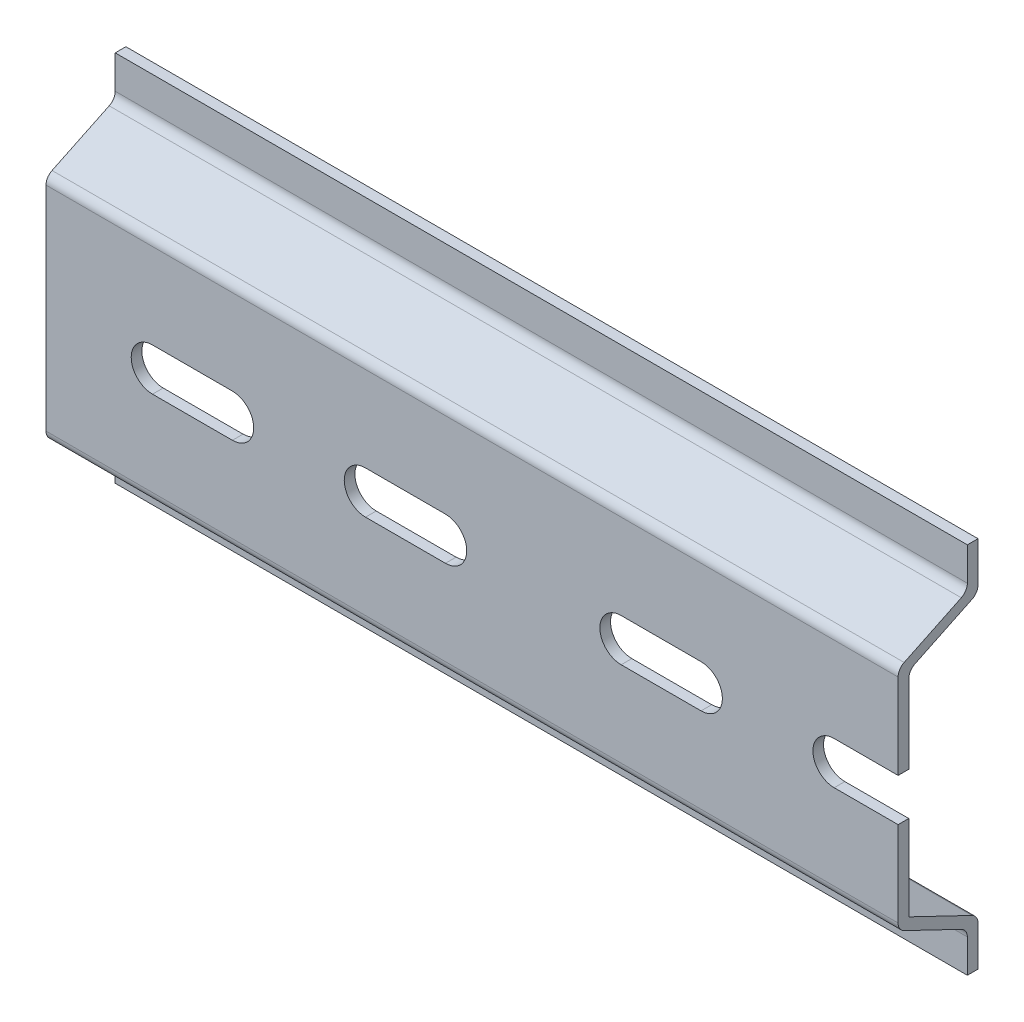
SolidWorks part; units mm, degrees
ref_plane "前视基准面" through (0, 0, 0) normal (0, 0, 1) x (1, 0, 0)
ref_plane "上视基准面" through (0, 0, 0) normal (0, 1, 0) x (1, 0, 0)
ref_plane "右视基准面" through (0, 0, 0) normal (1, 0, 0) x (0, 0, -1)
sketch "草图1" plane through (0, 0, 0) normal (1, 0, 0) x (0, 0, -1)
  line L0 (0, -10) -> (0, 10)
  line L1 (0, 10) -> (6.5, 13.1208)
  line L2 (6.5, 13.1208) -> (6.5, 17.5)
  line L3 (6.5, 17.5) -> (5.5, 17.5)
  line L4 (5.5, 17.5) -> (5.5, 13.75)
  line L5 (5.5, 13.75) -> (-1, 10.6292)
  line L6 (-1, 10.6292) -> (-1, -10.6292)
  line L7 (-14.3812, 0) -> (24.228, 0) construction
  line L8 (5.5, -13.75) -> (-1, -10.6292)
  line L9 (5.5, -17.5) -> (5.5, -13.75)
  line L10 (6.5, -17.5) -> (5.5, -17.5)
  line L11 (6.5, -13.1208) -> (6.5, -17.5)
  line L12 (0, -10) -> (6.5, -13.1208)
  point P12 (-1, 0)
  point P17 (0, 0)
  dimension "D1" = 7.5
  dimension "D2" = 1
  dimension "D3" = 1
  dimension "D4" = 1
  dimension "D5" = 27.5
  dimension "D6" = 35
  dimension "D7" = 20
extrude "凸台-拉伸1" add sketch "草图1" along normal blind 80
fillet "圆角1" radius 1 7 edges at (40, 13.75, -5.5) (40, 10.6292, 1) (40, 10, 0) (40, -10.6292, 1) (40, -13.1208, -6.5) (40, -13.75, -5.5) (40, 13.1208, -6.5)
sketch "草图2" plane through (0, 0, 0) normal (0, 0, -1) x (-1, 0, 0)
  line L0 (33.4315, 0) -> (-53.4315, 0) construction
  line L1 (-10, 0) -> (-17.5, 0) construction
  line L2 (-10, -2) -> (-17.5, -2)
  line L3 (-10, 2) -> (-17.5, 2)
  line L4 (-30, 0) -> (-37.5, 0) construction
  line L5 (-30, -2) -> (-37.5, -2)
  line L6 (-30, 2) -> (-37.5, 2)
  line L7 (-54, 0) -> (-61.5, 0) construction
  line L8 (-54, -2) -> (-61.5, -2)
  line L9 (-54, 2) -> (-61.5, 2)
  line L10 (-74, 0) -> (-81.5, 0) construction
  line L11 (-74, -2) -> (-81.5, -2)
  line L12 (-74, 2) -> (-81.5, 2)
  line L13 (-98, 0) -> (-105.5, 0) construction
  line L14 (-98, -2) -> (-105.5, -2)
  line L15 (-98, 2) -> (-105.5, 2)
  line L16 (-118, 0) -> (-125.5, 0) construction
  line L17 (-118, -2) -> (-125.5, -2)
  line L18 (-118, 2) -> (-125.5, 2)
  line L19 (-142, 0) -> (-149.5, 0) construction
  line L20 (-142, -2) -> (-149.5, -2)
  line L21 (-142, 2) -> (-149.5, 2)
  line L22 (-162, 0) -> (-169.5, 0) construction
  line L23 (-162, -2) -> (-169.5, -2)
  line L24 (-162, 2) -> (-169.5, 2)
  line L25 (-186, 0) -> (-193.5, 0) construction
  line L26 (-186, -2) -> (-193.5, -2)
  line L27 (-186, 2) -> (-193.5, 2)
  line L28 (-206, 0) -> (-213.5, 0) construction
  line L29 (-206, -2) -> (-213.5, -2)
  line L30 (-206, 2) -> (-213.5, 2)
  line L31 (-230, 0) -> (-237.5, 0) construction
  line L32 (-230, -2) -> (-237.5, -2)
  line L33 (-230, 2) -> (-237.5, 2)
  line L34 (-250, 0) -> (-257.5, 0) construction
  line L35 (-250, -2) -> (-257.5, -2)
  line L36 (-250, 2) -> (-257.5, 2)
  line L37 (-274, 0) -> (-281.5, 0) construction
  line L38 (-274, -2) -> (-281.5, -2)
  line L39 (-274, 2) -> (-281.5, 2)
  line L40 (-294, 0) -> (-301.5, 0) construction
  line L41 (-294, -2) -> (-301.5, -2)
  line L42 (-294, 2) -> (-301.5, 2)
  line L43 (-318, 0) -> (-325.5, 0) construction
  line L44 (-318, -2) -> (-325.5, -2)
  line L45 (-318, 2) -> (-325.5, 2)
  line L46 (-338, 0) -> (-345.5, 0) construction
  line L47 (-338, -2) -> (-345.5, -2)
  line L48 (-338, 2) -> (-345.5, 2)
  line L49 (-362, 0) -> (-369.5, 0) construction
  line L50 (-362, -2) -> (-369.5, -2)
  line L51 (-362, 2) -> (-369.5, 2)
  line L52 (-382, 0) -> (-389.5, 0) construction
  line L53 (-382, -2) -> (-389.5, -2)
  line L54 (-382, 2) -> (-389.5, 2)
  arc A0 (-10, -2) -> (-10, 2) centre (-10, 0) ccw
  arc A1 (-17.5, 2) -> (-17.5, -2) centre (-17.5, 0) ccw
  arc A2 (-30, -2) -> (-30, 2) centre (-30, 0) ccw
  arc A3 (-37.5, 2) -> (-37.5, -2) centre (-37.5, 0) ccw
  arc A4 (-54, -2) -> (-54, 2) centre (-54, 0) ccw
  arc A5 (-61.5, 2) -> (-61.5, -2) centre (-61.5, 0) ccw
  arc A6 (-74, -2) -> (-74, 2) centre (-74, 0) ccw
  arc A7 (-81.5, 2) -> (-81.5, -2) centre (-81.5, 0) ccw
  arc A8 (-98, -2) -> (-98, 2) centre (-98, 0) ccw
  arc A9 (-105.5, 2) -> (-105.5, -2) centre (-105.5, 0) ccw
  arc A10 (-118, -2) -> (-118, 2) centre (-118, 0) ccw
  arc A11 (-125.5, 2) -> (-125.5, -2) centre (-125.5, 0) ccw
  arc A12 (-142, -2) -> (-142, 2) centre (-142, 0) ccw
  arc A13 (-149.5, 2) -> (-149.5, -2) centre (-149.5, 0) ccw
  arc A14 (-162, -2) -> (-162, 2) centre (-162, 0) ccw
  arc A15 (-169.5, 2) -> (-169.5, -2) centre (-169.5, 0) ccw
  arc A16 (-186, -2) -> (-186, 2) centre (-186, 0) ccw
  arc A17 (-193.5, 2) -> (-193.5, -2) centre (-193.5, 0) ccw
  arc A18 (-206, -2) -> (-206, 2) centre (-206, 0) ccw
  arc A19 (-213.5, 2) -> (-213.5, -2) centre (-213.5, 0) ccw
  arc A20 (-230, -2) -> (-230, 2) centre (-230, 0) ccw
  arc A21 (-237.5, 2) -> (-237.5, -2) centre (-237.5, 0) ccw
  arc A22 (-250, -2) -> (-250, 2) centre (-250, 0) ccw
  arc A23 (-257.5, 2) -> (-257.5, -2) centre (-257.5, 0) ccw
  arc A24 (-274, -2) -> (-274, 2) centre (-274, 0) ccw
  arc A25 (-281.5, 2) -> (-281.5, -2) centre (-281.5, 0) ccw
  arc A26 (-294, -2) -> (-294, 2) centre (-294, 0) ccw
  arc A27 (-301.5, 2) -> (-301.5, -2) centre (-301.5, 0) ccw
  arc A28 (-318, -2) -> (-318, 2) centre (-318, 0) ccw
  arc A29 (-325.5, 2) -> (-325.5, -2) centre (-325.5, 0) ccw
  arc A30 (-338, -2) -> (-338, 2) centre (-338, 0) ccw
  arc A31 (-345.5, 2) -> (-345.5, -2) centre (-345.5, 0) ccw
  arc A32 (-362, -2) -> (-362, 2) centre (-362, 0) ccw
  arc A33 (-369.5, 2) -> (-369.5, -2) centre (-369.5, 0) ccw
  arc A34 (-382, -2) -> (-382, 2) centre (-382, 0) ccw
  arc A35 (-389.5, 2) -> (-389.5, -2) centre (-389.5, 0) ccw
  point P5 (-13.75, 0)
  point P14 (-33.75, 0)
  point P21 (-57.75, 0)
  point P28 (-77.75, 0)
  point P35 (-101.75, 0)
  point P42 (-121.75, 0)
  point P49 (-145.75, 0)
  point P56 (-165.75, 0)
  point P63 (-189.75, 0)
  point P70 (-209.75, 0)
  point P77 (-233.75, 0)
  point P84 (-253.75, 0)
  point P91 (-277.75, 0)
  point P98 (-297.75, 0)
  point P105 (-321.75, 0)
  point P112 (-341.75, 0)
  point P119 (-365.75, 0)
  point P126 (-385.75, 0)
  dimension "D1" = 2
  dimension "D2" = 7.5
  dimension "D3" = 10
  dimension "D4" = 2
  dimension "D5" = 9
extrude "切除-拉伸1" cut sketch "草图2" against normal blind 10
